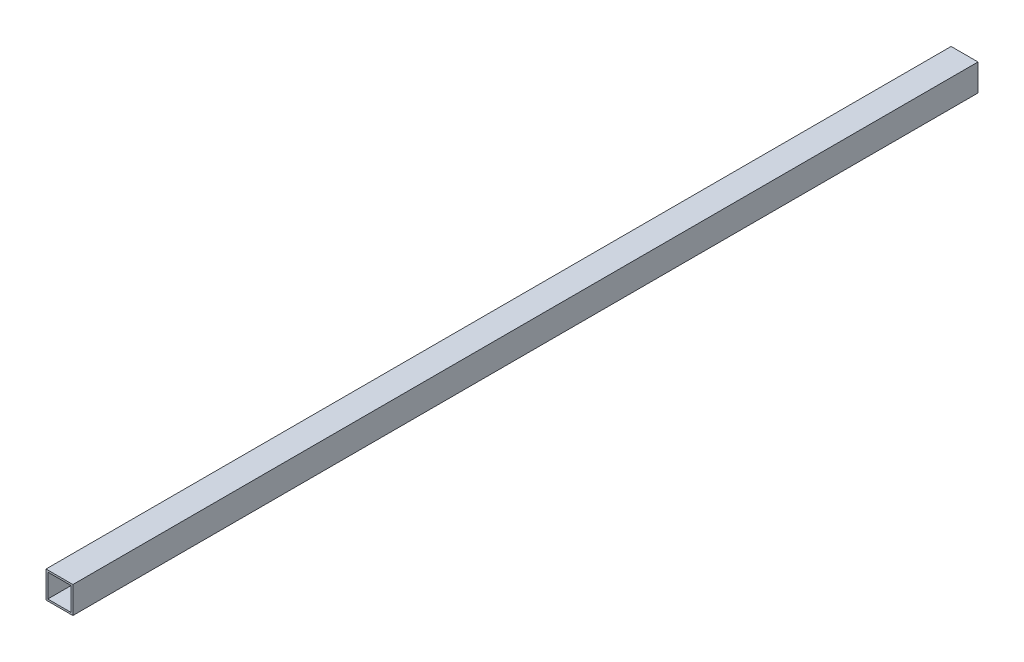
SolidWorks part; units mm, degrees
ref_plane "Alzado" through (0, 0, 0) normal (0, 0, 1) x (1, 0, 0)
ref_plane "Planta" through (0, 0, 0) normal (0, 1, 0) x (1, 0, 0)
ref_plane "Vista lateral" through (0, 0, 0) normal (1, 0, 0) x (0, 0, -1)
sketch "Croquis1" plane through (0, 0, 0) normal (0, 0, 1) x (1, 0, 0)
  line L1 (15, -15) -> (-15, -15)
  line L2 (15, -15) -> (15, 15)
  line L3 (15, 15) -> (-15, 15)
  line L4 (-15, -15) -> (-15, 15)
  line L5 (15, -15) -> (-15, 15) construction
  line L6 (15, 15) -> (-15, -15) construction
  point P0 (0, 0)
  dimension "D1" = 30
  dimension "D2" = 30
extrude "Extruir-Lámina1" add sketch "Croquis1" along normal blind 1010 thin
